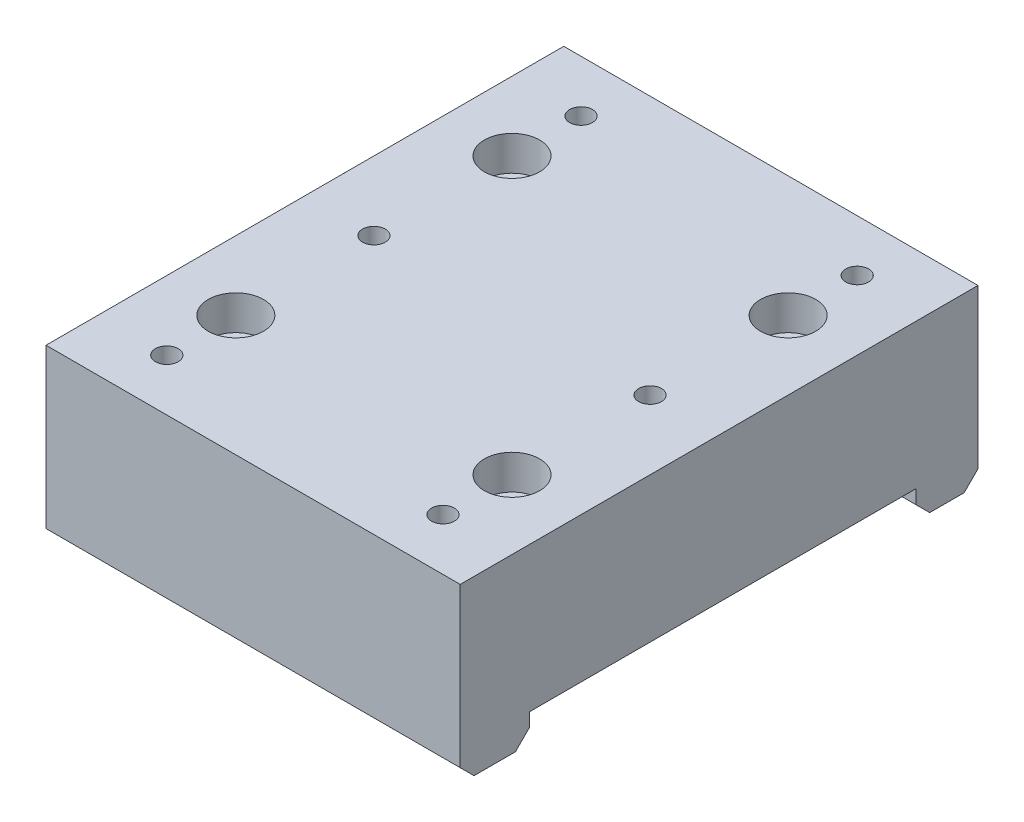
SolidWorks part; units mm, degrees
ref_plane "정면" through (0, 0, 0) normal (0, 0, 1) x (1, 0, 0)
ref_plane "윗면" through (0, 0, 0) normal (0, 1, 0) x (1, 0, 0)
ref_plane "우측면" through (0, 0, 0) normal (1, 0, 0) x (0, 0, -1)
sketch "스케치1" plane through (0, 0, 0) normal (0, 1, 0) x (1, 0, 0)
  line L1 (0, 0) -> (60, 0)
  line L2 (0, 0) -> (0, 75)
  line L3 (0, 75) -> (60, 75)
  line L4 (60, 0) -> (60, 75)
  dimension "D1" = 60
  dimension "D2" = 75
extrude "보스-돌출1" add sketch "스케치1" along normal blind 25
sketch "스케치2" plane through (60, 0, 0) normal (1, 0, 0) x (0, 0, -1)
  line L0 (0, 0) -> (75, 0) construction
  line L1 (10, 0) -> (66, 0)
  line L2 (10, 0) -> (10, 4)
  line L3 (10, 4) -> (66, 4)
  line L4 (66, 0) -> (66, 4)
  line L5 (0, 25) -> (0, 0) construction
  dimension "D1" = 56
  dimension "D2" = 10
  dimension "D3" = 4
extrude "컷-돌출1" cut sketch "스케치2" against normal through all
chamfer "모따기1" distance 2 angle 45 4 edges at (30, 0, -75) (30, 0, -66) (30, 0, 0) (30, 0, -10)
sketch "스케치3" plane through (0, 25, 0) normal (0, 1, 0) x (1, 0, 0)
  line L0 (0, 75) -> (0, 0) construction
  line L1 (0, 0) -> (60, 0) construction
  circle A0 centre (10, 57.5) radius 4
  circle A1 centre (10, 17.5) radius 4
  circle A2 centre (50, 57.5) radius 4
  circle A3 centre (50, 17.5) radius 4
  dimension "D3" = 8
  dimension "D1" = 10
  dimension "D2" = 40
  dimension "D4" = 17.5
  dimension "D5" = 40
extrude "컷-돌출2" cut sketch "스케치3" against normal blind 5
sketch "스케치4" plane through (0, 20, 0) normal (0, 1, 0) x (1, 0, 0)
  circle A0 centre (10, 57.5) radius 2.5
  circle A1 centre (50, 57.5) radius 2.5
  circle A2 centre (50, 17.5) radius 2.5
  circle A3 centre (10, 17.5) radius 2.5
  dimension "D1" = 5
extrude "컷-돌출3" cut sketch "스케치4" against normal through all
sketch "스케치5" plane through (0, 25, 0) normal (0, 1, 0) x (1, 0, 0)
  line L0 (0, 0) -> (60, 0) construction
  line L1 (0, 75) -> (0, 0) construction
  point P0 (10, 67.5)
  point P1 (10, 37.5)
  point P2 (10, 7.5)
  point P3 (50, 67.5)
  point P4 (50, 37.5)
  point P5 (50, 7.5)
  dimension "D1" = 7.5
  dimension "D2" = 10
  dimension "D3" = 40
  dimension "D4" = 30
  dimension "D5" = 30
hole_wizard "M4 나사 구멍1" positions "스케치5" profile "스케치6" tap size "M4" standard "ISO"
sketch "스케치6" plane through (10, 25, -67.5) normal (1, 0, 0) x (0, 0, 1)
  line L0 (0, 0) -> (0, 15.4914)
  line L1 (0, 15.4914) -> (1.65, 14.5)
  line L2 (1.65, 14.5) -> (1.65, 0)
  line L5 (1.65, 0) -> (0, 0)
  line L10 (0, 15.4914) -> (-1.65, 14.5) construction
  line L11 (0, -6.35) -> (0, 107.95) construction
  dimension "탭 드릴 지름" = 3.3
  dimension "탭 드릴 깊이" = 14.5
  dimension "드릴 각도" = 118
cosmetic thread "구멍 나사산1" parameters "D1"=8, "D2"=4
cosmetic thread "구멍 나사산2" parameters "D1"=8, "D2"=4
cosmetic thread "구멍 나사산3" parameters "D1"=8, "D2"=4
cosmetic thread "구멍 나사산4" parameters "D1"=8, "D2"=4
cosmetic thread "구멍 나사산5" parameters "D1"=8, "D2"=4
cosmetic thread "구멍 나사산6" parameters "D1"=8, "D2"=4
ref_plane "평면1" through (30, 0, 0) normal (1, 0, 0) x (0, 0, -1)
